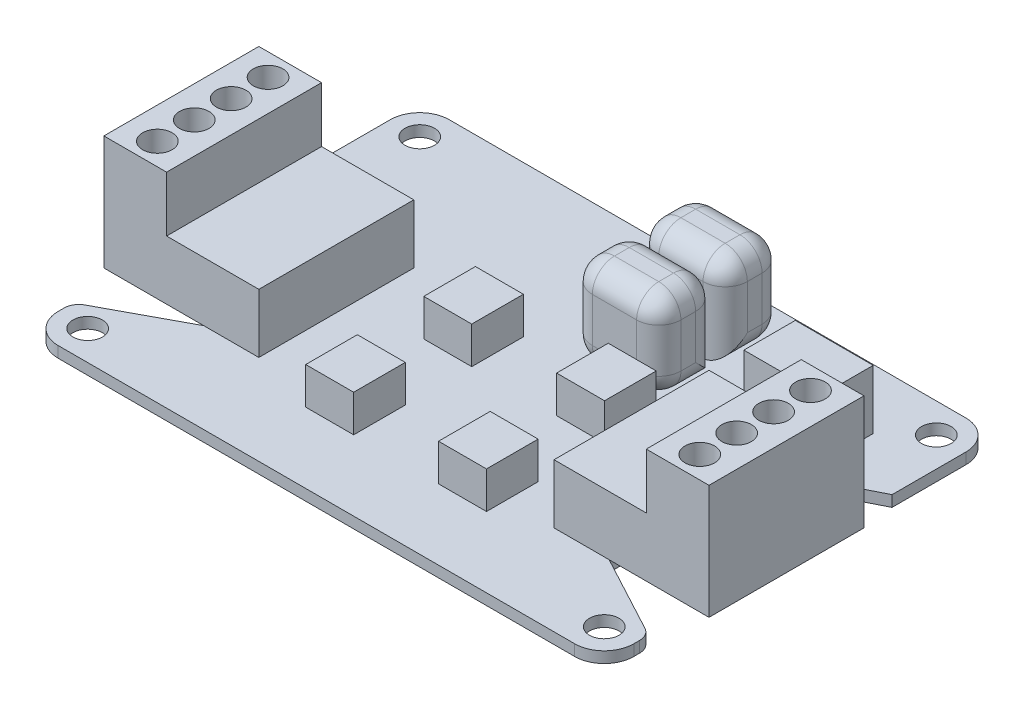
SolidWorks part; units mm, degrees
ref_plane "前视基准面" through (0, 0, 0) normal (0, 0, 1) x (1, 0, 0)
ref_plane "上视基准面" through (0, 0, 0) normal (0, 1, 0) x (1, 0, 0)
ref_plane "右视基准面" through (0, 0, 0) normal (1, 0, 0) x (0, 0, -1)
sketch "草图1" plane through (0, 0, 0) normal (0, 1, 0) x (1, 0, 0)
  line L0 (0, 4) -> (0, 4.8086)
  line L1 (4, 53) -> (74, 53)
  line L2 (78, 49) -> (78, 39)
  line L3 (74, 0) -> (4, 0)
  line L4 (0, 39) -> (11.5346, 33.1954)
  line L5 (11.5346, 33.1954) -> (11.5346, 12.1954)
  line L6 (11.5346, 12.1954) -> (1.0542, 6.5709)
  line L7 (0, 39) -> (0, 49)
  line L8 (39, 53) -> (39, 0) construction
  line L9 (78, 39) -> (66.4654, 33.1954)
  line L10 (66.4654, 12.1954) -> (76.9458, 6.5709)
  line L11 (66.4654, 33.1954) -> (66.4654, 12.1954)
  line L12 (78, 4.8086) -> (78, 4)
  arc A0 (78, 4) -> (74, 0) centre (74, 4) cw
  arc A1 (78, 49) -> (74, 53) centre (74, 49) ccw
  arc A2 (4, 0) -> (0, 4) centre (4, 4) cw
  arc A3 (0, 49) -> (4, 53) centre (4, 49) cw
  circle A4 centre (4, 49) radius 2
  circle A5 centre (4, 4) radius 2
  circle A6 centre (74, 49) radius 2
  circle A7 centre (74, 4) radius 2
  arc A8 (0, 4.8086) -> (1.0542, 6.5709) centre (2, 4.8086) cw
  arc A9 (78, 4.8086) -> (76.9458, 6.5709) centre (76, 4.8086) ccw
  point P9 (78, 53)
  point P12 (0, 0)
  point P15 (0, 53)
  dimension "D3" = 4
  dimension "D4" = 10
  dimension "D6" = 2
  dimension "D7" = 4
  dimension "D8" = 4
  dimension "D9" = 4
  dimension "D10" = 4
  dimension "D1" = 53
  dimension "D2" = 78
  dimension "D5" = 21
extrude "凸台-拉伸1" add sketch "草图1" along normal blind 1.5
sketch "草图2" plane through (0, 1.5, 0) normal (0, 1, 0) x (1, 0, 0)
  line L0 (19, 33.1954) -> (-2, 33.1954)
  line L1 (-2, 33.1954) -> (-2, 12.1954)
  line L2 (-2, 12.1954) -> (19, 12.1954)
  line L3 (19, 12.1954) -> (19, 33.1954)
  line L4 (0, 49) -> (0, 39) construction
  dimension "D1" = 2
  dimension "D2" = 21
extrude "凸台-拉伸2" add sketch "草图2" along normal blind 8 separate body
sketch "草图3" plane through (0, 9.5, 0) normal (0, 1, 0) x (1, 0, 0)
  line L0 (-2, 33.1954) -> (-2, 12.1954)
  line L1 (-2, 12.1954) -> (6.5, 12.1954)
  line L2 (-2, 12.1954) -> (19, 12.1954) construction
  line L3 (6.5, 12.1954) -> (6.5, 33.1954)
  line L4 (19, 33.1954) -> (-2, 33.1954) construction
  line L5 (6.5, 33.1954) -> (-2, 33.1954)
  dimension "D1" = 8.5
extrude "凸台-拉伸3" add sketch "草图3" along normal blind 7.5
sketch "草图4" plane through (0, 17, 0) normal (0, 1, 0) x (1, 0, 0)
  line L0 (6.5, 33.1954) -> (-2, 33.1954) construction
  circle A0 centre (2.25, 30.1954) radius 2
  circle A1 centre (2.25, 25.1954) radius 2
  circle A2 centre (2.25, 20.1954) radius 2
  circle A3 centre (2.25, 15.1954) radius 2
  dimension "D1" = 4
  dimension "D2" = 3
extrude "切除-拉伸1" cut sketch "草图4" against normal blind 3
ref_plane "基准面1" through (39, 0, 0) normal (1, 0, 0) x (0, 0, -1)
mirror "镜向1" about plane through (39, 0, 0) normal (1, 0, 0) of "凸台-拉伸2", "凸台-拉伸3", "切除-拉伸1"
sketch "草图5" plane through (0, 1.5, 0) normal (0, 1, 0) x (1, 0, 0)
  line L0 (59, 37.9219) -> (59, 44.8943)
  line L1 (59, 44.8943) -> (69.5501, 44.8943)
  line L2 (69.5501, 44.8943) -> (69.5501, 37.9219)
  line L3 (69.5501, 37.9219) -> (59, 37.9219)
extrude "凸台-拉伸4" add sketch "草图5" along normal blind 8
sketch "草图6" plane through (0, 1.5, 0) normal (0, 1, 0) x (1, 0, 0)
  line L0 (28.0025, 32.5409) -> (28.0025, 25.5409)
  line L1 (28.0025, 25.5409) -> (34.5025, 25.5409)
  line L2 (34.5025, 25.5409) -> (34.5025, 32.5409)
  line L3 (34.5025, 32.5409) -> (28.0025, 32.5409)
  line L4 (52.5025, 32.5409) -> (46.0025, 32.5409)
  line L5 (46.0025, 32.5409) -> (46.0025, 25.5409)
  line L6 (46.0025, 25.5409) -> (52.5025, 25.5409)
  line L7 (52.5025, 25.5409) -> (52.5025, 32.5409)
  line L8 (52.5025, 16.5409) -> (46.0025, 16.5409)
  line L9 (46.0025, 16.5409) -> (46.0025, 9.5409)
  line L10 (46.0025, 9.5409) -> (52.5025, 9.5409)
  line L11 (52.5025, 9.5409) -> (52.5025, 16.5409)
  line L12 (34.5025, 16.5409) -> (28.0025, 16.5409)
  line L13 (28.0025, 16.5409) -> (28.0025, 9.5409)
  line L14 (28.0025, 9.5409) -> (34.5025, 9.5409)
  line L15 (34.5025, 9.5409) -> (34.5025, 16.5409)
  dimension "D1" = 7
  dimension "D2" = 6.5
  dimension "D3" = 2
  dimension "D4" = 2
extrude "凸台-拉伸5" add sketch "草图6" along normal blind 5 separate body
sketch "草图7" plane through (0, 1.5, 0) normal (0, 1, 0) x (1, 0, 0)
  line L0 (52.1926, 33.1954) -> (40.1926, 33.1954)
  line L1 (40.1926, 33.1954) -> (40.1926, 41.1954)
  line L2 (40.1926, 41.1954) -> (52.1926, 41.1954)
  line L3 (52.1926, 41.1954) -> (52.1926, 33.1954)
  line L4 (52.1926, 50.1954) -> (52.1926, 42.1954)
  line L5 (52.1926, 42.1954) -> (40.1926, 42.1954)
  line L6 (40.1926, 42.1954) -> (40.1926, 50.1954)
  line L7 (40.1926, 50.1954) -> (52.1926, 50.1954)
  dimension "D1" = 8
  dimension "D2" = 12
  dimension "D3" = 2
extrude "凸台-拉伸6" add sketch "草图7" along normal blind 12 separate body
fillet "圆角1" radius 3 11 edges at (40.1926, 7.5, -42.1954) (40.1926, 1.5, -46.1954) (40.1926, 7.5, -50.1954) (46.1926, 1.5, -50.1954) (52.1926, 7.5, -42.1954) (52.1926, 7.5, -50.1954) (52.1926, 1.5, -46.1954) (40.1926, 13.5, -46.1954) (46.1926, 13.5, -50.1954) (52.1926, 13.5, -46.1954) (46.1926, 13.5, -42.1954)
fillet "圆角2" radius 3 11 edges at (52.1926, 7.5, -41.1954) (52.1926, 1.5, -37.1954) (46.1926, 13.5, -41.1954) (52.1926, 13.5, -37.1954) (46.1926, 13.5, -33.1954) (52.1926, 7.5, -33.1954) (46.1926, 1.5, -33.1954) (40.1926, 7.5, -41.1954) (40.1926, 13.5, -37.1954) (40.1926, 7.5, -33.1954) (40.1926, 1.5, -37.1954)
